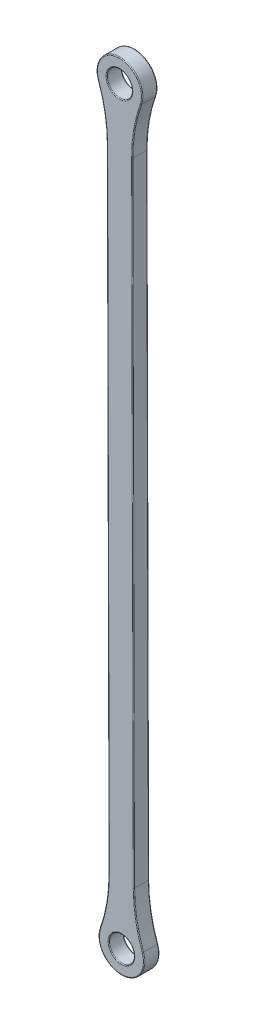
SolidWorks part; units mm, degrees
ref_plane "Front Plane" through (0, 0, 0) normal (0, 0, 1) x (1, 0, 0)
ref_plane "Top Plane" through (0, 0, 0) normal (0, 1, 0) x (1, 0, 0)
ref_plane "Right Plane" through (0, 0, 0) normal (1, 0, 0) x (0, 0, -1)
sketch "Sketch1" plane through (0, 0, 0) normal (0, 0, 1) x (1, 0, 0)
  line L0 (14.5, 81.5) -> (14.1075, 229.4995) construction
  line L1 (14.5, 81.5) -> (14.1075, 229.4995) construction
  line L2 (14.5, 81.5) -> (14.1075, 229.4995) construction
  line L3 (12, 81.4934) -> (11.6075, 229.4928)
  line L4 (17, 81.5066) -> (16.6075, 229.5061)
  circle A0 centre (14.1075, 229.4995) radius 4.5
  circle A1 centre (14.5, 81.5) radius 4.5
  arc A2 (12, 81.4934) -> (17, 81.5066) centre (14.5, 81.5) ccw
  arc A3 (16.6075, 229.5061) -> (11.6075, 229.4928) centre (14.1075, 229.4995) ccw
  arc A4 (12, 81.4934) -> (17, 81.5066) centre (14.5, 81.5) cw
  arc A5 (11.6075, 229.4928) -> (16.6075, 229.5061) centre (14.1075, 229.4995) ccw
  arc A6 (11.6174, 225.7512) -> (16.6174, 225.7645) centre (14.1075, 229.4995) cw
  arc A7 (16.9901, 85.2483) -> (11.9901, 85.235) centre (14.5, 81.5) cw
  point P5 (14.3038, 155.4997)
  dimension "D1" = 9
  dimension "D2" = 9
  dimension "D3" = 5
extrude "Boss-Extrude1" add sketch "Sketch1" against normal blind 3 contours A3 L4 A0 L3 | A1 L4 A0 L3 | A5 L3 A0 L4 | L3 A4 L4 A1 | A2 L3 A1 L4
fillet "Fillet1" radius 30 4 edges at (16.9901, 85.2483, -1.5) (11.9901, 85.235, -1.5) (11.6174, 225.7512, -1.5) (16.6174, 225.7645, -1.5)
fillet "Fillet2" radius 0.15 20 edges at (17, 81.5, -3) (17, 81.5, 0) (16.6075, 229.4995, -3) (16.6075, 229.4995, 0) (11.1867, 223.0234, -3) (11.1867, 223.0234, 0) (14.0956, 233.9995, -3) (14.0956, 233.9995, 0) (17.0626, 223.039, -3) (17.0626, 223.039, 0) (16.8037, 155.5064, 0) (16.8037, 155.5064, -3) (17.4208, 87.9761, -3) (17.4208, 87.9761, 0) (14.5119, 77, -3) (14.5119, 77, 0) (11.5449, 87.9605, -3) (11.5449, 87.9605, 0) (11.8038, 155.4931, -3) (11.8038, 155.4931, 0)
